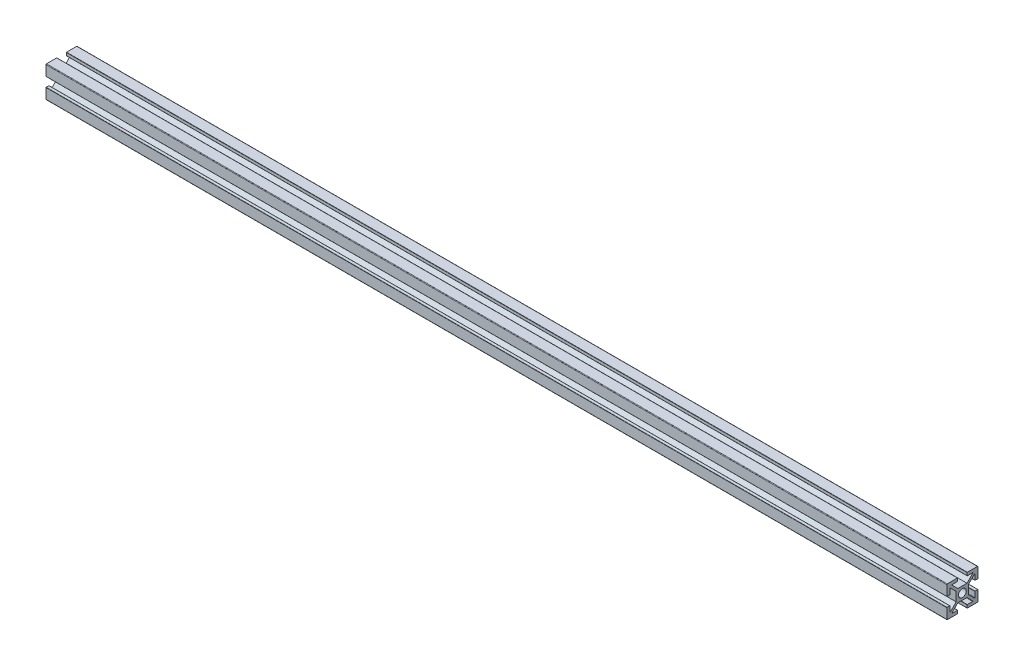
SolidWorks part; units mm, degrees
ref_plane "Front Plane" through (0, 0, 0) normal (0, 0, 1) x (1, 0, 0)
ref_plane "Top Plane" through (0, 0, 0) normal (0, 1, 0) x (1, 0, 0)
ref_plane "Right Plane" through (0, 0, 0) normal (1, 0, 0) x (0, 0, -1)
sketch "Sketch1" plane through (0, 0, 0) normal (1, 0, 0) x (0, 0, -1)
  line L0 (-27.5327, 12.6519) -> (-25.8327, 12.6519)
  line L1 (-20.8327, 19.6519) -> (-27.3327, 19.6519)
  line L2 (-27.6827, 12.8019) -> (-27.6827, 19.3019)
  line L3 (-14.7033, 13.6519) -> (-20.5696, 13.6519)
  line L4 (-21.6364, 6.7065) -> (-21.6364, 12.5973)
  line L5 (-25.6827, 12.8019) -> (-25.6827, 16.2381)
  line L6 (-24.2508, 17.6519) -> (-20.8327, 17.6519)
  line L7 (-20.6827, 17.8019) -> (-20.6827, 19.5019)
  line L8 (-25.6827, 17.6519) -> (-21.6364, 13.6519) construction
  line L9 (-25.4273, 16.3447) -> (-21.6364, 12.5973)
  line L10 (-24.3563, 17.3952) -> (-20.5696, 13.6519)
  line L11 (-9.5901, 17.6519) -> (-13.6364, 13.6519) construction
  line L12 (-17.6364, 9.6519) -> (-17.6364, 21.3405) construction
  line L13 (-17.6364, 9.6519) -> (-32.6206, 9.6519) construction
  line L14 (-10.9166, 17.3952) -> (-14.7033, 13.6519)
  line L15 (-9.8456, 16.3447) -> (-13.6364, 12.5973)
  line L16 (-14.5901, 17.8019) -> (-14.5901, 19.5019)
  line L17 (-11.0221, 17.6519) -> (-14.4401, 17.6519)
  line L18 (-9.5901, 12.8019) -> (-9.5901, 16.2381)
  line L19 (-13.6364, 6.7065) -> (-13.6364, 12.5973)
  line L20 (-7.5901, 12.8019) -> (-7.5901, 19.3019)
  line L21 (-14.4401, 19.6519) -> (-7.9401, 19.6519)
  line L22 (-7.7401, 12.6519) -> (-9.4401, 12.6519)
  line L23 (-9.5901, 1.6519) -> (-13.6364, 5.6519) construction
  line L24 (-25.6827, 1.6519) -> (-21.6364, 5.6519) construction
  line L25 (-7.7401, 6.6519) -> (-9.4401, 6.6519)
  line L26 (-14.4401, -0.3481) -> (-7.9401, -0.3481)
  line L27 (-7.5901, 6.5019) -> (-7.5901, 0.0019)
  line L28 (-9.5901, 6.5019) -> (-9.5901, 3.0657)
  line L29 (-11.0221, 1.6519) -> (-14.4401, 1.6519)
  line L30 (-14.5901, 1.5019) -> (-14.5901, -0.1981)
  line L31 (-9.8456, 2.959) -> (-13.6364, 6.7065)
  line L32 (-10.9166, 1.9085) -> (-14.7033, 5.6519)
  line L33 (-24.3563, 1.9085) -> (-20.5696, 5.6519)
  line L34 (-25.4273, 2.959) -> (-21.6364, 6.7065)
  line L35 (-20.6827, 1.5019) -> (-20.6827, -0.1981)
  line L36 (-24.2508, 1.6519) -> (-20.8327, 1.6519)
  line L37 (-25.6827, 6.5019) -> (-25.6827, 3.0657)
  line L38 (-14.7033, 5.6519) -> (-20.5696, 5.6519)
  line L39 (-27.6827, 6.5019) -> (-27.6827, 0.0019)
  line L40 (-20.8327, -0.3481) -> (-27.3327, -0.3481)
  line L41 (-27.5327, 6.6519) -> (-25.8327, 6.6519)
  circle A0 centre (-17.6364, 9.6519) radius 2.5
  arc A1 (-27.6827, 19.3019) -> (-27.3327, 19.6519) centre (-27.3327, 19.3019) cw
  arc A2 (-27.5327, 12.6519) -> (-27.6827, 12.8019) centre (-27.5327, 12.8019) cw
  arc A3 (-25.8327, 12.6519) -> (-25.6827, 12.8019) centre (-25.8327, 12.8019) ccw
  arc A4 (-20.8327, 19.6519) -> (-20.6827, 19.5019) centre (-20.8327, 19.5019) cw
  arc A5 (-20.8327, 17.6519) -> (-20.6827, 17.8019) centre (-20.8327, 17.8019) ccw
  arc A6 (-24.3563, 17.3952) -> (-24.2508, 17.6519) centre (-24.2508, 17.5019) cw
  arc A7 (-25.4273, 16.3447) -> (-25.6827, 16.2381) centre (-25.5327, 16.2381) ccw
  arc A8 (-9.8456, 16.3447) -> (-9.5901, 16.2381) centre (-9.7401, 16.2381) cw
  arc A9 (-10.9166, 17.3952) -> (-11.0221, 17.6519) centre (-11.0221, 17.5019) ccw
  arc A10 (-14.4401, 17.6519) -> (-14.5901, 17.8019) centre (-14.4401, 17.8019) cw
  arc A11 (-14.4401, 19.6519) -> (-14.5901, 19.5019) centre (-14.4401, 19.5019) ccw
  arc A12 (-9.4401, 12.6519) -> (-9.5901, 12.8019) centre (-9.4401, 12.8019) cw
  arc A13 (-7.7401, 12.6519) -> (-7.5901, 12.8019) centre (-7.7401, 12.8019) ccw
  arc A14 (-7.5901, 19.3019) -> (-7.9401, 19.6519) centre (-7.9401, 19.3019) ccw
  arc A15 (-7.5901, 0.0019) -> (-7.9401, -0.3481) centre (-7.9401, 0.0019) cw
  arc A16 (-7.7401, 6.6519) -> (-7.5901, 6.5019) centre (-7.7401, 6.5019) cw
  arc A17 (-9.4401, 6.6519) -> (-9.5901, 6.5019) centre (-9.4401, 6.5019) ccw
  arc A18 (-14.4401, -0.3481) -> (-14.5901, -0.1981) centre (-14.4401, -0.1981) cw
  arc A19 (-14.4401, 1.6519) -> (-14.5901, 1.5019) centre (-14.4401, 1.5019) ccw
  arc A20 (-10.9166, 1.9085) -> (-11.0221, 1.6519) centre (-11.0221, 1.8019) cw
  arc A21 (-9.8456, 2.959) -> (-9.5901, 3.0657) centre (-9.7401, 3.0657) ccw
  arc A22 (-25.4273, 2.959) -> (-25.6827, 3.0657) centre (-25.5327, 3.0657) cw
  arc A23 (-24.3563, 1.9085) -> (-24.2508, 1.6519) centre (-24.2508, 1.8019) ccw
  arc A24 (-20.8327, 1.6519) -> (-20.6827, 1.5019) centre (-20.8327, 1.5019) cw
  arc A25 (-20.8327, -0.3481) -> (-20.6827, -0.1981) centre (-20.8327, -0.1981) ccw
  arc A26 (-25.8327, 6.6519) -> (-25.6827, 6.5019) centre (-25.8327, 6.5019) cw
  arc A27 (-27.5327, 6.6519) -> (-27.6827, 6.5019) centre (-27.5327, 6.5019) ccw
  arc A28 (-27.6827, 0.0019) -> (-27.3327, -0.3481) centre (-27.3327, 0.0019) ccw
  point P27 (-14.5901, 17.6519)
  point P28 (-7.5901, -0.3481)
  point P47 (-13.6364, 9.6519)
  point P57 (-17.6364, 13.6519)
  point P59 (-14.5901, 19.6519)
  point P60 (-9.5901, 12.6519)
  point P61 (-7.5901, 12.6519)
  point P62 (-7.5901, 19.6519)
  point P112 (-21.6364, 9.6519)
  point P113 (-7.5901, 6.6519)
  point P114 (-9.5901, 6.6519)
  point P115 (-14.5901, -0.3481)
  point P116 (-17.6364, 5.6519)
  point P117 (-20.6827, 1.6519)
  point P118 (-20.6827, -0.3481)
  point P119 (-25.6827, 6.6519)
  point P120 (-14.5901, 1.6519)
  point P121 (-27.6827, 6.6519)
  point P122 (-27.6827, -0.3481)
extrude "Boss-Extrude1" add sketch "Sketch1" along normal blind 580
sketch "Sketch7" plane through (0, 13.6519, 0) normal (0, 1, 0) x (1, 0, 0)
  line L0 (0, -17.6364) -> (580, -17.6364) construction
  line L1 (0, -14.7033) -> (0, -20.5696) construction
  line L2 (580, -14.7033) -> (580, -20.5696) construction
  circle A0 centre (20, -17.6364) radius 2
  circle A2 centre (458, -17.6364) radius 2
  circle A4 centre (518, -17.6364) radius 2
  circle A5 centre (560, -17.6364) radius 2
  circle A6 centre (62, -17.6364) radius 2
  circle A7 centre (122, -17.6364) radius 2
  circle A8 centre (165, -17.6364) radius 2
  circle A10 centre (290, -17.6364) radius 2
  circle A11 centre (415, -17.6364) radius 2
  point P6 (20, -17.6364)
  point P8 (458, -17.6364)
  dimension "D6" = 4
  dimension "D7" = 4
  dimension "D8" = 4
  dimension "D9" = 4
  dimension "D10" = 4
  dimension "D11" = 42
  dimension "D12" = 4
  dimension "D4" = 20
  dimension "D5" = 42
  dimension "D3" = 4
  dimension "D2" = 60
  dimension "D13" = 4
  dimension "D14" = 60
  dimension "D15" = 125
  dimension "D16" = 4
  dimension "D17" = 125
  dimension "D1" = 20
extrude "Cut-Extrude1" cut sketch "Sketch7" against normal blind 3
